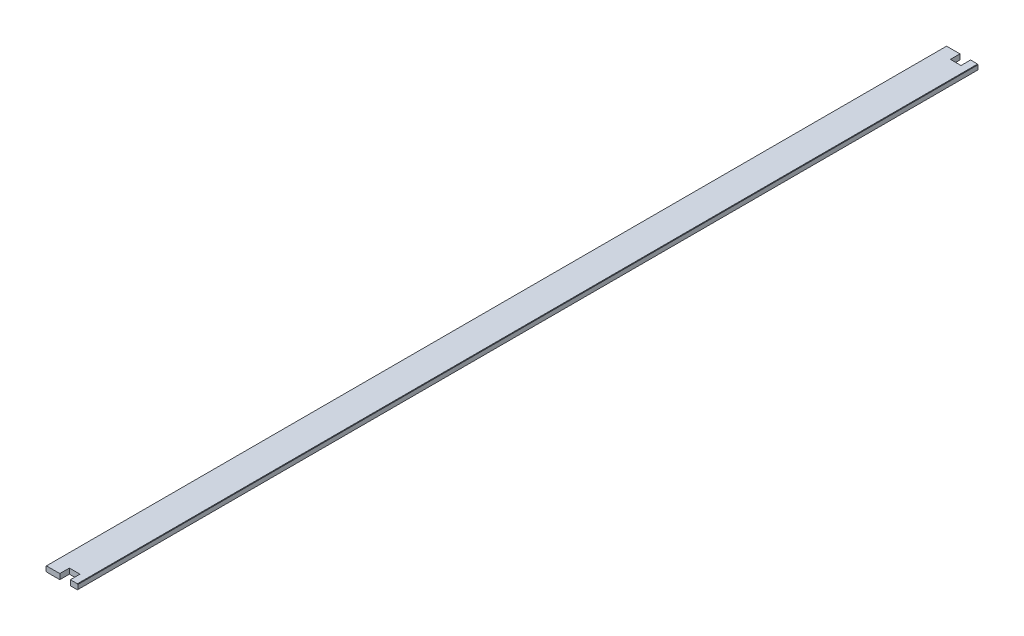
SolidWorks part; units mm, degrees
ref_plane "Спереди" through (0, 0, 0) normal (0, 0, 1) x (1, 0, 0)
ref_plane "Сверху" through (0, 0, 0) normal (0, 1, 0) x (1, 0, 0)
ref_plane "Справа" through (0, 0, 0) normal (1, 0, 0) x (0, 0, -1)
sketch "Эскиз1" plane through (0, 0, 0) normal (0, 0, 1) x (1, 0, 0)
  line L0 (-75, 10.5) -> (-73, 12.5)
  line L1 (-73, 12.5) -> (73, 12.5)
  line L2 (-75, 10.5) -> (-75, -10.5)
  line L3 (-73, -12.5) -> (73, -12.5)
  line L4 (75, 10.5) -> (75, -10.5)
  line L5 (-75, 12.5) -> (75, -12.5) construction
  line L6 (-75, -12.5) -> (75, 12.5) construction
  line L7 (-75, -10.5) -> (-73, -12.5)
  line L8 (73, -12.5) -> (75, -10.5)
  line L9 (73, 12.5) -> (75, 10.5)
  point P0 (0, 0)
  dimension "D1" = 150
  dimension "D2" = 25
extrude "Бобышка-Вытянуть1" add sketch "Эскиз1" along normal blind 4240
sketch "Эскиз2" plane through (0, 12.5, 0) normal (0, 1, 0) x (1, 0, 0)
  line L0 (73, 0) -> (-73, 0) construction
  line L1 (-10, 0) -> (40, 0)
  line L2 (-10, 0) -> (-10, -45)
  line L3 (-10, -45) -> (40, -45)
  line L4 (40, 0) -> (40, -45)
  line L5 (-75, -4240) -> (-75, 0) construction
  line L6 (73, -4240) -> (-73, -4240) construction
  line L7 (-10, -4240) -> (40, -4240)
  line L8 (-10, -4240) -> (-10, -4195)
  line L9 (-10, -4195) -> (40, -4195)
  line L10 (40, -4240) -> (40, -4195)
  dimension "D1" = 50
  dimension "D2" = 45
  dimension "D3" = 65
  dimension "D4" = 45
  dimension "D5" = 50
  dimension "D6" = 65
extrude "Вырез-Вытянуть1" cut sketch "Эскиз2" against normal through all
